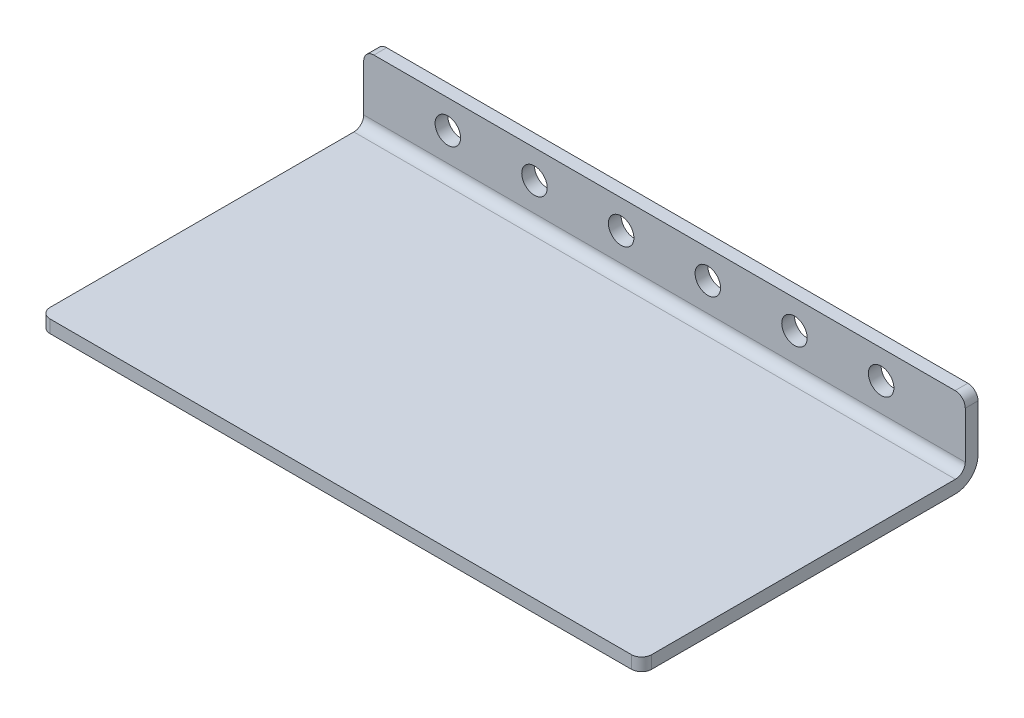
SolidWorks part; units mm, degrees
ref_plane "Front Plane" through (0, 0, 0) normal (0, 0, 1) x (1, 0, 0)
ref_plane "Top Plane" through (0, 0, 0) normal (0, 1, 0) x (1, 0, 0)
ref_plane "Right Plane" through (0, 0, 0) normal (1, 0, 0) x (0, 0, -1)
sketch "Sketch1" plane through (0, 0, 0) normal (1, 0, 0) x (0, 0, -1)
  line L0 (-25.1756, 0) -> (13.919, 0)
  line L1 (55, 0) -> (-55, 0) construction
  line L2 (16.7344, 2.8154) -> (16.7344, 9.906)
  line L3 (-25.1756, 1.5875) -> (13.919, 1.5875)
  line L4 (15.1469, 2.8154) -> (15.1469, 9.906)
  line L5 (-25.1756, 1.5875) -> (-25.1756, 0)
  line L6 (15.1469, 9.906) -> (16.7344, 9.906)
  arc A0 (13.919, 0) -> (16.7344, 2.8154) centre (13.919, 2.8154) ccw
  arc A1 (13.919, 1.5875) -> (15.1469, 2.8154) centre (13.919, 2.8154) ccw
  dimension "D2" = 41.91
  dimension "D3" = 9.906
  dimension "D1" = 1.5875
extrude "Boss-Extrude1" add sketch "Sketch1" along normal blind 37.465 and the other way blind 37.465
fillet "Fillet1" radius 1.27 4 edges at (37.465, 9.906, -15.9407) (-37.465, 9.906, -15.9407) (-37.465, 0.7937, 25.1756) (37.465, 0.7937, 25.1756)
sketch "Sketch2" plane through (0, 0, -16.7344) normal (0, 0, -1) x (-1, 0, 0)
  line L0 (26.9875, 6.3607) -> (-26.9875, 6.3607) construction
  line L2 (0, 5.4483) -> (0, -5.4483) construction
  line L3 (0, 9.906) -> (0, 2.8154) construction
  line L4 (36.195, 9.906) -> (-36.195, 9.906) construction
  line L5 (37.465, 2.8154) -> (-37.465, 2.8154) construction
  circle A0 centre (-26.9875, 6.3607) radius 1.5875
  circle A1 centre (-16.1925, 6.3607) radius 1.5875
  circle A2 centre (-5.3975, 6.3607) radius 1.5875
  circle A3 centre (5.3975, 6.3607) radius 1.5875
  circle A4 centre (16.1925, 6.3607) radius 1.5875
  circle A5 centre (26.9875, 6.3607) radius 1.5875
  point P3 (0, 6.3607)
  point P11 (-7.1, 6.3607)
  point P13 (0, 0)
  dimension "D3" = 3.175
  dimension "D1" = 53.975
  dimension "D2" = 6
extrude "Cut-Extrude1" cut sketch "Sketch2" against normal through all
